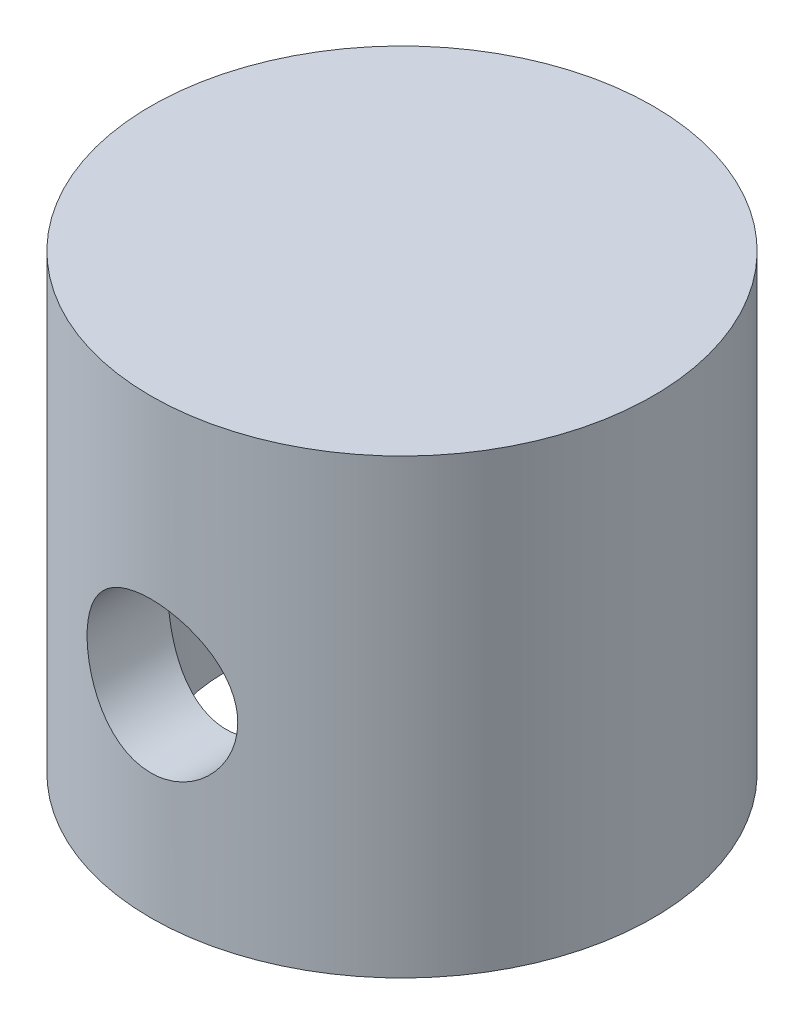
SolidWorks part; units mm, degrees
ref_plane "Front Plane" through (0, 0, 0) normal (0, 0, 1) x (1, 0, 0)
ref_plane "Top Plane" through (0, 0, 0) normal (0, 1, 0) x (1, 0, 0)
ref_plane "Right Plane" through (0, 0, 0) normal (1, 0, 0) x (0, 0, -1)
sketch "Sketch1" plane through (0, 0, 0) normal (0, 1, 0) x (1, 0, 0)
  circle A0 centre (0, 0) radius 10
  dimension "D1" = 20
extrude "Boss-Extrude1" add sketch "Sketch1" along normal blind 18
sketch "Sketch2" plane through (0, 0, 0) normal (0, -1, 0) x (-1, 0, 0)
  circle A0 centre (0, 0) radius 7
  dimension "D1" = 14
extrude "Cut-Extrude1" cut sketch "Sketch2" against normal blind 15
sketch "Sketch4" plane through (0, 0, 0) normal (0, 0, 1) x (1, 0, 0)
  line L0 (0, -9.9) -> (0, 9.9) construction
  circle A0 centre (0, 8) radius 3
  dimension "D1" = 6
extrude "Cut-Extrude3" cut sketch "Sketch4" against normal through all both and the other way through all
fillet "Fillet1" radius 1 1 edges at (0, 15, -7)
